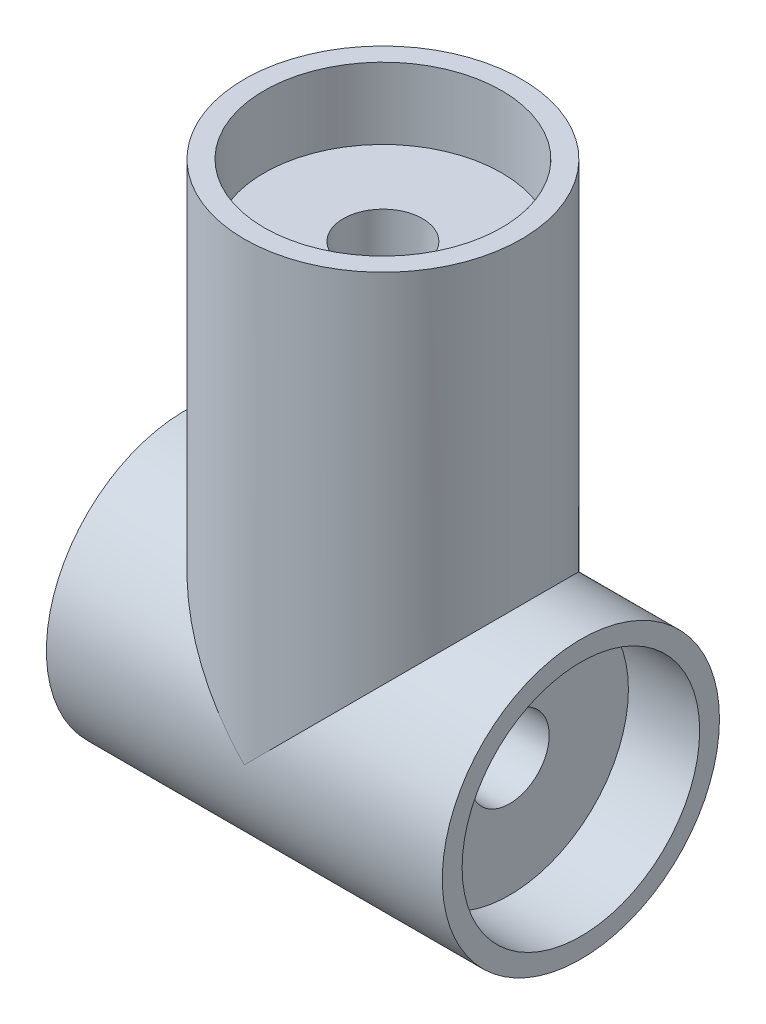
SolidWorks part; units mm, degrees
material "EN8"
ref_plane "Front Plane" through (0, 0, 0) normal (0, 0, 1) x (1, 0, 0)
ref_plane "Top Plane" through (0, 0, 0) normal (0, 1, 0) x (1, 0, 0)
ref_plane "Right Plane" through (0, 0, 0) normal (1, 0, 0) x (0, 0, -1)
sketch "Sketch2" plane through (0, 0, 0) normal (1, 0, 0) x (0, 0, -1)
  circle A0 centre (0, 0) radius 17.5
  circle A1 centre (0, 0) radius 5
  dimension "D1" = 35
  dimension "D2" = 10
extrude "Boss-Extrude1" add sketch "Sketch2" along normal mid plane 50
sketch "Sketch3" plane through (25, 0, 0) normal (1, 0, 0) x (0, 0, -1)
  circle A0 centre (0, 0) radius 5 construction
  circle A3 centre (0, 0) radius 5
  circle A4 centre (0, 0) radius 15
  dimension "D2" = 30
extrude "Cut-Extrude1" cut sketch "Sketch3" against normal blind 9
mirror "Mirror1" about plane through (0, 0, 0) normal (1, 0, 0) of "Cut-Extrude1"
sketch "Sketch4" plane through (0, 0, 0) normal (1, 0, 0) x (0, 0, -1)
  line L0 (0, 17.5) -> (0, 57.5)
  circle A1 centre (0, 0) radius 17.5 construction
  dimension "D1" = 40
ref_plane "Plane1" through (0, 57.5, 0) normal (0, 1, 0) x (1, 0, 0)
sketch "Sketch5" plane through (0, 57.5, 0) normal (0, 1, 0) x (1, 0, 0)
  circle A0 centre (0, 0) radius 17.5
  circle A1 centre (0, 0) radius 5
  dimension "D1" = 35
  dimension "D2" = 10
extrude "Boss-Extrude2" add sketch "Sketch5" against normal up to surface (57.5 mm away) up to face at (25, 0, -17.5)
sketch "Sketch6" plane through (0, 57.5, 0) normal (0, 1, 0) x (1, 0, 0)
  circle A0 centre (0, 0) radius 5 construction
  circle A1 centre (0, 0) radius 5
  circle A2 centre (0, 0) radius 15
  dimension "D1" = 30
extrude "Cut-Extrude2" cut sketch "Sketch6" against normal blind 9
